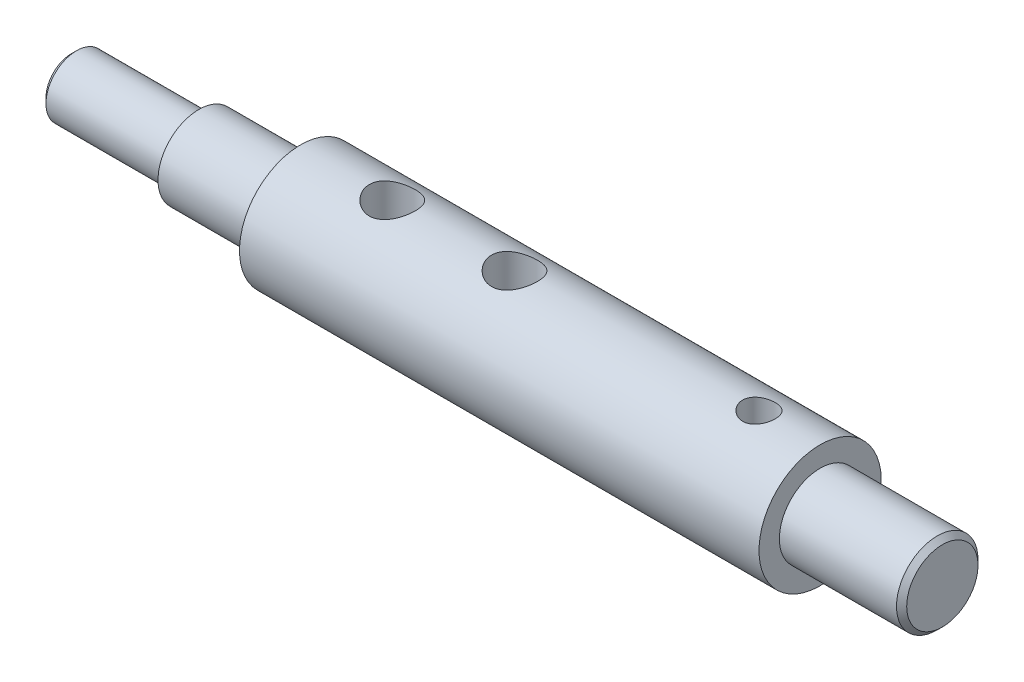
SolidWorks part; units mm, degrees
ref_plane "Alzado" through (0, 0, 0) normal (1, 0, 0) x (0, 1, 0)
ref_plane "Planta" through (0, 0, 0) normal (0, 0, 1) x (0, 1, 0)
ref_plane "Vista lateral" through (0, 0, 0) normal (0, 1, 0) x (-1, 0, 0)
sketch "Croquis1" plane through (0, 0, 0) normal (0, 1, 0) x (-1, 0, 0)
  line L7 (-42.75, 0) -> (42.75, 0) construction
  line L13 (-42.75, 0) -> (42.75, 0)
  line L18 (-42.75, 0) -> (-42.75, 4)
  line L21 (-42.75, 4) -> (-30.75, 4)
  line L22 (-30.75, 4) -> (-30.75, 6)
  line L23 (-30.75, 6) -> (20.25, 6)
  line L24 (20.25, 6) -> (20.25, 4)
  line L27 (30.25, 3) -> (42.75, 3)
  line L28 (42.75, 3) -> (42.75, 0)
  line L29 (20.25, 4) -> (30.25, 4)
  line L30 (30.25, 4) -> (30.25, 3)
  dimension "D2" = 10
  dimension "D3" = 8
  dimension "D4" = 12
  dimension "D5" = 51
  dimension "D6" = 3
  dimension "D7" = 4
  dimension "D11" = 12
  dimension "D12" = 22.5
revolve "Revolución1" add sketch "Croquis1" angle 360 about L7
chamfer "Chaflán1" distance 0.5 angle 45 2 edges at (-42.75, 0, -3) (42.75, 0, -4)
ref_plane "Plano2" through (0, 10, 0) normal (0, 1, 0) x (-1, 0, 0)
sketch "Croquis3" plane through (0, 10, 0) normal (0, 1, 0) x (-1, 0, 0)
  line L0 (-30.75, 0) -> (20.25, 0) construction
  line L1 (-30.75, 6) -> (-30.75, -6) construction
  line L2 (20.25, -6) -> (20.25, 6) construction
  point P6 (-24.75, 0)
  point P7 (-0.75, 0)
  point P8 (11.25, 0)
  dimension "D1" = 6
  dimension "D2" = 9
  dimension "D3" = 12
hole_wizard "Taladro de margen para M41" positions "Croquis3" profile "Croquis4" hole size "M4" standard "Ansi Metric"
sketch "Croquis4" plane through (-11.25, 10, 0) normal (1, 0, 0) x (0, 0, 1)
  line L0 (0, 0) -> (0, 16)
  line L1 (0, 16) -> (2.25, 16)
  line L2 (2.25, 16) -> (2.25, 0)
  line L5 (2.25, 0) -> (0, 0)
  line L11 (0, -6.35) -> (0, 107.95) construction
  dimension "Diámetro de taladro hasta el siguiente" = 4.5
  dimension "Profundidad de taladro hasta el siguiente" = 16
chamfer "Chaflán2" [suppressed] distance 1 angle 45
sketch "Croquis5" plane through (0, 10, 0) normal (0, 1, 0) x (-1, 0, 0)
  point P0 (-24.75, 0)
hole_wizard "Taladro de margen para M31" positions "Croquis5" profile "Croquis6" hole size "M3" standard "DIN" end condition through all
sketch "Croquis6" plane through (24.75, 10, 0) normal (1, 0, 0) x (0, 0, 1)
  line L0 (0, 0) -> (0, 16)
  line L1 (0, 16) -> (1.6, 16)
  line L2 (1.6, 16) -> (1.6, 0)
  line L5 (1.6, 0) -> (0, 0)
  line L11 (0, -6.35) -> (0, 107.95) construction
  dimension "Diámetro de taladro hasta el siguiente" = 3.2
  dimension "Profundidad de taladro hasta el siguiente" = 16
equation "\"ancho_circlip\"=0.8"
equation "\"ranura_circlip\"=0.45"
